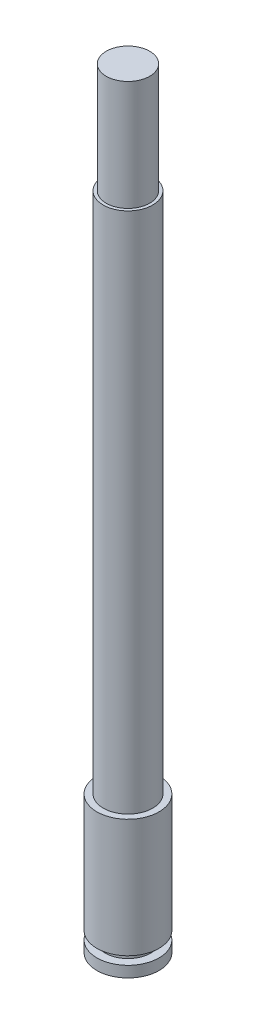
SolidWorks part; units mm, degrees
ref_plane "Front Plane" through (0, 0, 0) normal (0, 0, 1) x (1, 0, 0)
ref_plane "Top Plane" through (0, 0, 0) normal (0, 1, 0) x (1, 0, 0)
ref_plane "Right Plane" through (0, 0, 0) normal (1, 0, 0) x (0, 0, -1)
sketch "Sketch1" plane through (0, 0, 0) normal (0, 1, 0) x (1, 0, 0)
  line L0 (0, 0) -> (0, 3.3) construction
  line L1 (0, 0) -> (-6.2902, 0) construction
  circle A0 centre (0, 0) radius 5.65
  dimension "D1" = 11.3
extrude "Boss-Extrude1" add sketch "Sketch1" along normal blind 2 contours A0
sketch "Sketch2" plane through (0, 2, 0) normal (0, 1, 0) x (1, 0, 0)
  circle A0 centre (0, 0) radius 4.15
  dimension "D1" = 8.3
extrude "Boss-Extrude2" add sketch "Sketch2" along normal blind 1.5
sketch "Sketch3" plane through (0, 3.5, 0) normal (0, 1, 0) x (1, 0, 0)
  circle A0 centre (0, 0) radius 5.65
  dimension "D1" = 11.3
extrude "Boss-Extrude3" add sketch "Sketch3" along normal blind 21.5
sketch "Sketch4" plane through (0, 25, 0) normal (0, 1, 0) x (1, 0, 0)
  circle A0 centre (0, 0) radius 4.5
  dimension "D1" = 9
extrude "Boss-Extrude4" add sketch "Sketch4" along normal blind 30 contours A0
sketch "Sketch5" plane through (0, 55, 0) normal (0, 1, 0) x (1, 0, 0)
  circle A0 centre (0, 0) radius 4.5
  dimension "D1" = 9
extrude "Boss-Extrude5" add sketch "Sketch5" along normal blind 65
sketch "Sketch6" plane through (0, 120, 0) normal (0, 1, 0) x (1, 0, 0)
  circle A0 centre (0, 0) radius 3.95
  dimension "D1" = 7.9
extrude "Boss-Extrude6" add sketch "Sketch6" along normal blind 20
